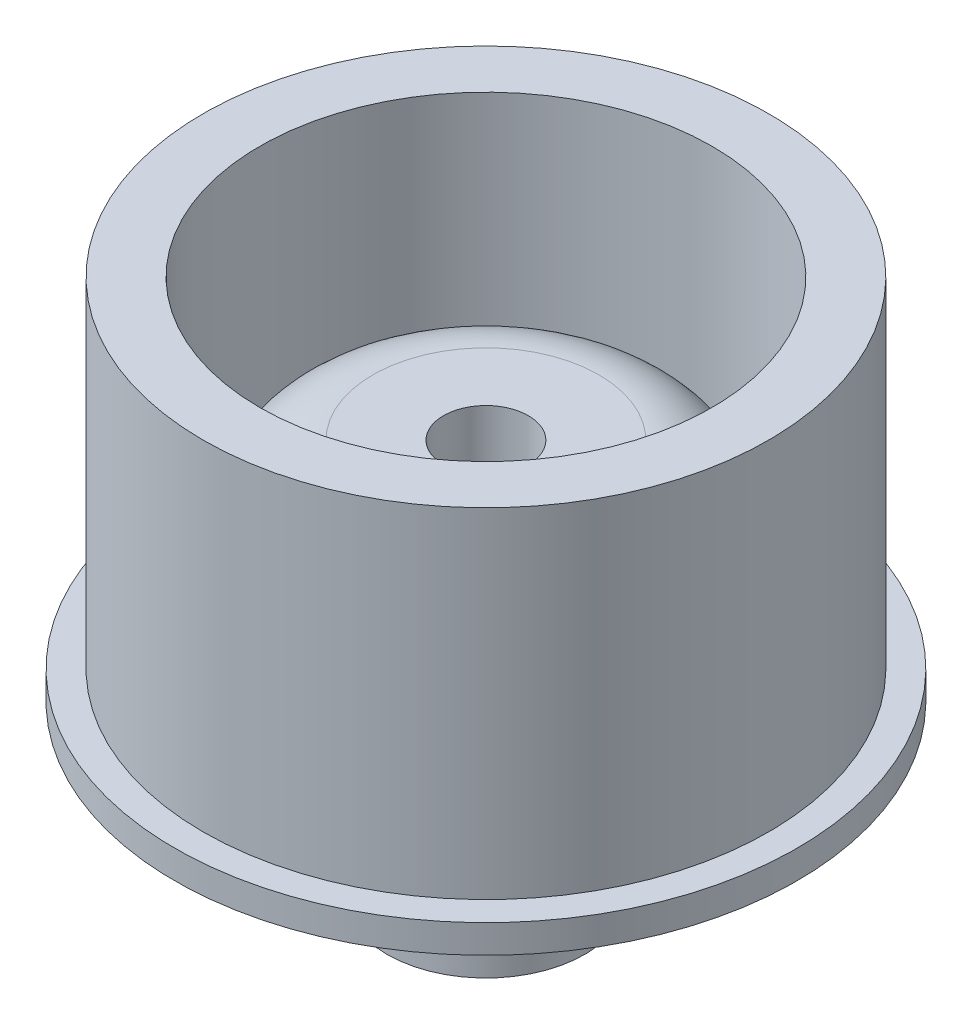
SolidWorks part; units mm, degrees
ref_plane "正面" through (0, 0, 0) normal (0, 0, 1) x (1, 0, 0)
ref_plane "平面" through (0, 0, 0) normal (0, 1, 0) x (1, 0, 0)
ref_plane "右側面" through (0, 0, 0) normal (1, 0, 0) x (0, 0, -1)
sketch "ｽｹｯﾁ1" plane through (0, 0, 0) normal (0, 1, 0) x (1, 0, 0)
  circle A0 centre (0, 0) radius 10
  dimension "D1" = 20
extrude "ﾎﾞｽ - 押し出し1" add sketch "ｽｹｯﾁ1" along normal blind 12
sketch "ｽｹｯﾁ2" plane through (0, 0, 0) normal (0, -1, 0) x (1, 0, 0)
  circle A0 centre (0, 0) radius 11
  circle A1 centre (0, 0) radius 10
  circle A2 centre (0, 0) radius 10 construction
  dimension "D2" = 22
  dimension "D1" = 0
extrude "ﾎﾞｽ - 押し出し2" add sketch "ｽｹｯﾁ2" along normal blind 1
sketch "ｽｹｯﾁ3" plane through (0, -1, 0) normal (0, -1, 0) x (1, 0, 0)
  circle A0 centre (0, 0) radius 5
  circle A1 centre (0, 0) radius 11
  circle A2 centre (0, 0) radius 11 construction
  circle A3 centre (0, 0) radius 3.5
  dimension "D2" = 10
  dimension "D3" = 7
  dimension "D1" = 0
extrude "ｶｯﾄ - 押し出し1" cut sketch "ｽｹｯﾁ3" against normal blind 6 and the other way through all
sketch "ｽｹｯﾁ5" plane through (0, -1, 0) normal (0, -1, 0) x (1, 0, 0)
  circle A1 centre (0, 0) radius 3.5
  circle A2 centre (0, 0) radius 3.5
  dimension "D1" = 0
extrude "ﾎﾞｽ - 押し出し3" add sketch "ｽｹｯﾁ5" along normal blind 6
shell "ｼｪﾙ1" thickness 2
fillet "ﾌｨﾚｯﾄ1" radius 3 1 edges at (0, 7, -7)
